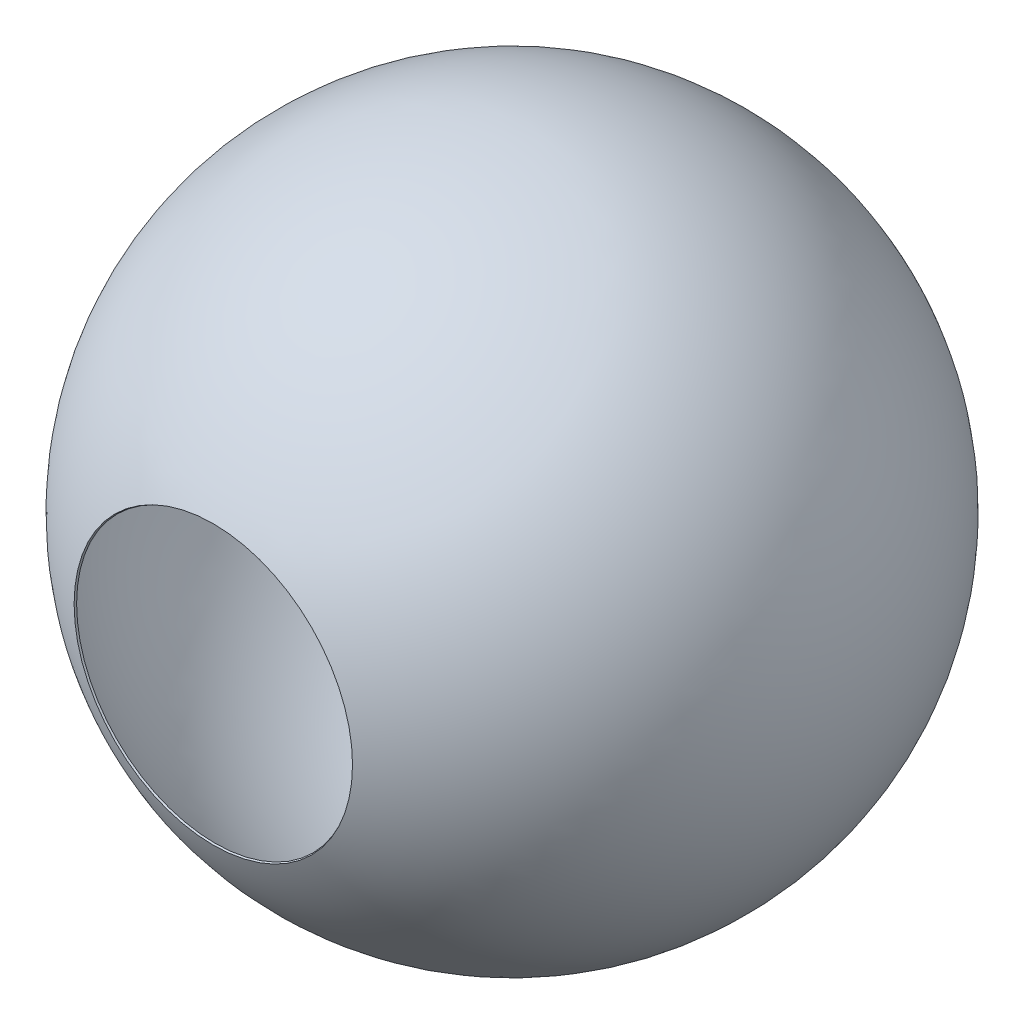
SolidWorks part; units mm, degrees
ref_plane "Front Plane" through (0, 0, 0) normal (0, 0, 1) x (1, 0, 0)
ref_plane "Top Plane" through (0, 0, 0) normal (0, 1, 0) x (1, 0, 0)
ref_plane "Right Plane" through (0, 0, 0) normal (1, 0, 0) x (0, 0, -1)
sketch "Sketch1" plane through (0, 0, 0) normal (1, 0, 0) x (0, 0, -1)
  line L0 (528.5016, 124.6399) -> (528.5016, 0)
  line L3 (-495, 230.6517) -> (-495, 0) construction
  line L4 (-492.1901, 229.3424) -> (0, 0) construction
  line L5 (-495, 230.6517) -> (-492.1901, 229.3424)
  line L6 (-495, 0) -> (531.6016, 0) construction
  line L7 (531.6016, 125) -> (531.6016, 0)
  line L8 (528.5016, 0) -> (531.6016, 0)
  arc A0 (531.6016, 125) -> (-495, 230.6517) centre (0, 0) ccw
  arc A1 (528.5016, 124.6399) -> (-492.1901, 229.3424) centre (0, 0) ccw
  dimension "D2" = 543
  dimension "D3" = 495
  dimension "D4" = 125
  dimension "D5" = 3.1
revolve "Shell" add sketch "Sketch1" angle 360 about L6
sketch "Picture Sketch" plane through (0, 0, 0) normal (0, 0, 1) x (1, 0, 0)
  line L0 (-356.5753, -20.7815) -> (269.657, 26.3052) construction
  line L1 (0, 543) -> (0, -543) construction
  line L2 (0, 0) -> (271.5, 470.2518) construction
  line L3 (0, 0) -> (-271.5, 470.2518) construction
  line L4 (-543, 0) -> (543, 0) construction
  line L5 (0, 0) -> (457.9616, -291.7537) construction
  line L6 (0, 0) -> (-457.9616, -291.7537) construction
  circle A0 centre (0, 0) radius 543
equation "\"PressureHull_InnerRadius\"= 546.1mm"
equation "\"PressureHull_OuterRadius\"= 609.6mm"
equation "\"InnerShell_InnerRadius\"= 543mm"
